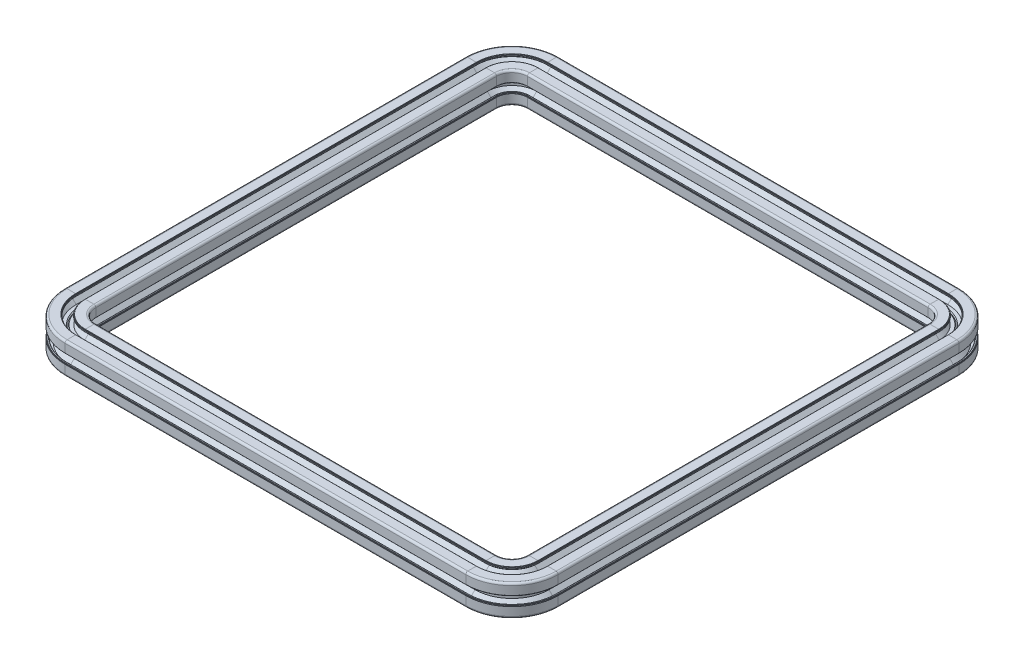
SolidWorks part; units mm, degrees
material "AISI 1020"
ref_plane "Alzado" through (0, 0, 0) normal (0, 0, 1) x (1, 0, 0)
ref_plane "Planta" through (0, 0, 0) normal (0, 1, 0) x (1, 0, 0)
ref_plane "Vista lateral" through (0, 0, 0) normal (1, 0, 0) x (0, 0, -1)
sketch "Croquis1" plane through (0, 0, 0) normal (0, 1, 0) x (1, 0, 0)
  line L5 (-225, 0) -> (225, 0) construction
  line L10 (225, -195) -> (225, 195)
  line L18 (-225, 195) -> (-225, -195)
  line L39 (-195, 225) -> (195, 225)
  line L40 (-195, -225) -> (195, -225)
  arc A8 (-195, -225) -> (-225, -195) centre (-195, -195) cw
  arc A9 (225, -195) -> (195, -225) centre (195, -195) cw
  arc A10 (225, 195) -> (195, 225) centre (195, 195) ccw
  arc A11 (-195, 225) -> (-225, 195) centre (-195, 195) ccw
  point P2 (0, 0)
  point P3 (0, 0)
  point P18 (-225, -225)
  point P21 (250, -250)
  point P24 (225, 225)
  point P27 (-225, 225)
  dimension "D7" = 30
  dimension "D4" = 450
  dimension "D6" = 450
other " C:\\PROGRAM FILES\\SOLIDWORKS CORP\\SOLIDWORKS\\DATA\\WELDMENT PROFILES\\BOSCH\\ALUMINIO\\BOSCH_PERFIL 30 X 30 - FALTA(1)"
ref_plane "Plano1" through (-225, 0, -195) normal (0, 0, 1) x (1, 0, 0)
sketch "Sketch1" plane through (-225, 0, -195) normal (0, 0, 1) x (1, 0, 0)
  line L0 (-13, 15) -> (-15, 15) construction
  line L1 (-15, 13) -> (-15, 15) construction
  line L2 (13, 15) -> (15, 15) construction
  line L3 (15, 13) -> (15, 15) construction
  line L4 (-4.75, 15) -> (4.75, 15) construction
  line L5 (-4.75, -15) -> (4.75, -15) construction
  line L6 (-15, 4.75) -> (-15, -4.75) construction
  line L7 (15, 4.75) -> (15, -4.75) construction
  line L8 (-15, -13) -> (-15, -15) construction
  line L9 (-13, -15) -> (-15, -15) construction
  line L10 (15, -13) -> (15, -15) construction
  line L11 (13, -15) -> (15, -15) construction
  line L12 (0, 5.4849) -> (0, 15) construction
  line L13 (0, -5.4849) -> (0, -15) construction
  line L14 (5.4849, 0) -> (15, 0) construction
  line L15 (-5.4849, 0) -> (-15, 0) construction
  line L24 (-0.9, -6) -> (0, -5.4849)
  line L25 (0, -5.4849) -> (0.9, -6)
  line L26 (0.9, -6) -> (4.2045, -6)
  line L27 (4.2045, -6) -> (8.25, -10.05)
  line L28 (8.25, -10.05) -> (8.25, -12.6)
  line L29 (8.05, -12.8) -> (4.65, -12.8)
  line L30 (4.05, -13.4) -> (4.05, -14.3)
  line L31 (4.25, -14.5) -> (4.35, -14.5)
  line L32 (4.55, -14.7) -> (4.55, -14.8)
  line L33 (4.75, -15) -> (13, -15)
  line L34 (15, -13) -> (15, -4.75)
  line L35 (14.8, -4.55) -> (14.7, -4.55)
  line L36 (14.5, -4.35) -> (14.5, -4.25)
  line L37 (14.3, -4.05) -> (13.4, -4.05)
  line L38 (12.8, -4.65) -> (12.8, -8.05)
  line L39 (12.6, -8.25) -> (10.05, -8.25)
  line L40 (10.05, -8.25) -> (6.0045, -4.2045)
  line L41 (6.0045, -4.2045) -> (6.0045, -0.9)
  line L42 (6.0045, -0.9) -> (5.4849, 0)
  line L43 (5.4849, 0) -> (6.0045, 0.9)
  line L44 (6.0045, 0.9) -> (6.0045, 4.2045)
  line L45 (6.0045, 4.2045) -> (10.05, 8.25)
  line L46 (10.05, 8.25) -> (12.6, 8.25)
  line L47 (12.8, 8.05) -> (12.8, 4.65)
  line L48 (13.4, 4.05) -> (14.3, 4.05)
  line L49 (14.5, 4.25) -> (14.5, 4.35)
  line L50 (14.7, 4.55) -> (14.8, 4.55)
  line L51 (15, 4.75) -> (15, 13)
  line L52 (13, 15) -> (4.75, 15)
  line L53 (4.55, 14.8) -> (4.55, 14.7)
  line L54 (4.35, 14.5) -> (4.25, 14.5)
  line L55 (4.05, 14.3) -> (4.05, 13.4)
  line L56 (4.65, 12.8) -> (8.05, 12.8)
  line L57 (8.25, 12.6) -> (8.25, 10.05)
  line L58 (8.25, 10.05) -> (4.2045, 6)
  line L59 (4.2045, 6) -> (0.9, 6)
  line L60 (0.9, 6) -> (0, 5.4849)
  line L61 (0, 5.4849) -> (-0.9, 6)
  line L62 (-0.9, 6) -> (-4.2045, 6)
  line L63 (-4.2045, 6) -> (-8.25, 10.05)
  line L64 (-8.25, 10.05) -> (-8.25, 12.6)
  line L65 (-8.05, 12.8) -> (-4.65, 12.8)
  line L66 (-4.05, 13.4) -> (-4.05, 14.3)
  line L67 (-4.25, 14.5) -> (-4.35, 14.5)
  line L68 (-4.55, 14.7) -> (-4.55, 14.8)
  line L69 (-4.75, 15) -> (-13, 15)
  line L70 (-15, 13) -> (-15, 4.75)
  line L71 (-14.8, 4.55) -> (-14.7, 4.55)
  line L72 (-14.5, 4.35) -> (-14.5, 4.25)
  line L73 (-14.3, 4.05) -> (-13.4, 4.05)
  line L74 (-12.8, 4.65) -> (-12.8, 8.05)
  line L75 (-12.6, 8.25) -> (-10.05, 8.25)
  line L76 (-10.05, 8.25) -> (-6.0045, 4.2045)
  line L77 (-6.0045, 4.2045) -> (-6.0045, 0.9)
  line L78 (-6.0045, 0.9) -> (-5.4849, 0)
  line L79 (-5.4849, 0) -> (-6.0045, -0.9)
  line L80 (-6.0045, -0.9) -> (-6.0045, -4.2045)
  line L81 (-6.0045, -4.2045) -> (-10.05, -8.25)
  line L82 (-10.05, -8.25) -> (-12.6, -8.25)
  line L83 (-12.8, -8.05) -> (-12.8, -4.65)
  line L84 (-13.4, -4.05) -> (-14.3, -4.05)
  line L85 (-14.5, -4.25) -> (-14.5, -4.35)
  line L86 (-14.7, -4.55) -> (-14.8, -4.55)
  line L87 (-15, -4.75) -> (-15, -13)
  line L88 (-13, -15) -> (-4.75, -15)
  line L89 (-4.55, -14.8) -> (-4.55, -14.7)
  line L90 (-4.35, -14.5) -> (-4.25, -14.5)
  line L91 (-4.05, -14.3) -> (-4.05, -13.4)
  line L92 (-4.65, -12.8) -> (-8.05, -12.8)
  line L93 (-8.25, -12.6) -> (-8.25, -10.05)
  line L94 (-8.25, -10.05) -> (-4.2045, -6)
  line L95 (-4.2045, -6) -> (-0.9, -6)
  circle A0 centre (0, 0) radius 3.65
  arc A20 (8.05, -12.8) -> (8.25, -12.6) centre (8.05, -12.6) ccw
  arc A21 (4.65, -12.8) -> (4.05, -13.4) centre (4.65, -13.4) ccw
  arc A22 (4.05, -14.3) -> (4.25, -14.5) centre (4.25, -14.3) ccw
  arc A23 (4.55, -14.7) -> (4.35, -14.5) centre (4.35, -14.7) ccw
  arc A24 (4.55, -14.8) -> (4.75, -15) centre (4.75, -14.8) ccw
  arc A25 (13, -15) -> (15, -13) centre (13, -13) ccw
  arc A26 (15, -4.75) -> (14.8, -4.55) centre (14.8, -4.75) ccw
  arc A27 (14.5, -4.35) -> (14.7, -4.55) centre (14.7, -4.35) ccw
  arc A28 (14.5, -4.25) -> (14.3, -4.05) centre (14.3, -4.25) ccw
  arc A29 (13.4, -4.05) -> (12.8, -4.65) centre (13.4, -4.65) ccw
  arc A30 (12.6, -8.25) -> (12.8, -8.05) centre (12.6, -8.05) ccw
  arc A31 (12.8, 8.05) -> (12.6, 8.25) centre (12.6, 8.05) ccw
  arc A32 (12.8, 4.65) -> (13.4, 4.05) centre (13.4, 4.65) ccw
  arc A33 (14.3, 4.05) -> (14.5, 4.25) centre (14.3, 4.25) ccw
  arc A34 (14.7, 4.55) -> (14.5, 4.35) centre (14.7, 4.35) ccw
  arc A35 (14.8, 4.55) -> (15, 4.75) centre (14.8, 4.75) ccw
  arc A36 (15, 13) -> (13, 15) centre (13, 13) ccw
  arc A37 (4.75, 15) -> (4.55, 14.8) centre (4.75, 14.8) ccw
  arc A38 (4.35, 14.5) -> (4.55, 14.7) centre (4.35, 14.7) ccw
  arc A39 (4.25, 14.5) -> (4.05, 14.3) centre (4.25, 14.3) ccw
  arc A40 (4.05, 13.4) -> (4.65, 12.8) centre (4.65, 13.4) ccw
  arc A41 (8.25, 12.6) -> (8.05, 12.8) centre (8.05, 12.6) ccw
  arc A42 (-8.05, 12.8) -> (-8.25, 12.6) centre (-8.05, 12.6) ccw
  arc A43 (-4.65, 12.8) -> (-4.05, 13.4) centre (-4.65, 13.4) ccw
  arc A44 (-4.05, 14.3) -> (-4.25, 14.5) centre (-4.25, 14.3) ccw
  arc A45 (-4.55, 14.7) -> (-4.35, 14.5) centre (-4.35, 14.7) ccw
  arc A46 (-4.55, 14.8) -> (-4.75, 15) centre (-4.75, 14.8) ccw
  arc A47 (-13, 15) -> (-15, 13) centre (-13, 13) ccw
  arc A48 (-15, 4.75) -> (-14.8, 4.55) centre (-14.8, 4.75) ccw
  arc A49 (-14.5, 4.35) -> (-14.7, 4.55) centre (-14.7, 4.35) ccw
  arc A50 (-14.5, 4.25) -> (-14.3, 4.05) centre (-14.3, 4.25) ccw
  arc A51 (-13.4, 4.05) -> (-12.8, 4.65) centre (-13.4, 4.65) ccw
  arc A52 (-12.6, 8.25) -> (-12.8, 8.05) centre (-12.6, 8.05) ccw
  arc A53 (-12.8, -8.05) -> (-12.6, -8.25) centre (-12.6, -8.05) ccw
  arc A54 (-12.8, -4.65) -> (-13.4, -4.05) centre (-13.4, -4.65) ccw
  arc A55 (-14.3, -4.05) -> (-14.5, -4.25) centre (-14.3, -4.25) ccw
  arc A56 (-14.7, -4.55) -> (-14.5, -4.35) centre (-14.7, -4.35) ccw
  arc A57 (-14.8, -4.55) -> (-15, -4.75) centre (-14.8, -4.75) ccw
  arc A58 (-15, -13) -> (-13, -15) centre (-13, -13) ccw
  arc A59 (-4.75, -15) -> (-4.55, -14.8) centre (-4.75, -14.8) ccw
  arc A60 (-4.35, -14.5) -> (-4.55, -14.7) centre (-4.35, -14.7) ccw
  arc A61 (-4.25, -14.5) -> (-4.05, -14.3) centre (-4.25, -14.3) ccw
  arc A62 (-4.05, -13.4) -> (-4.65, -12.8) centre (-4.65, -13.4) ccw
  arc A63 (-8.25, -12.6) -> (-8.05, -12.8) centre (-8.05, -12.6) ccw
  point P9 (-15, 15)
  point P11 (0, 15)
  point P14 (15, 15)
  point P20 (0, -15)
  point P26 (-15, 0)
  point P30 (15, 0)
  point P32 (-15, -15)
  point P35 (15, -15)
  point P39 (0, 0)
equation "\"Ancho_llanta\"= 44mm"
equation "\"Diametro_llanta\"= 197.51mm"
